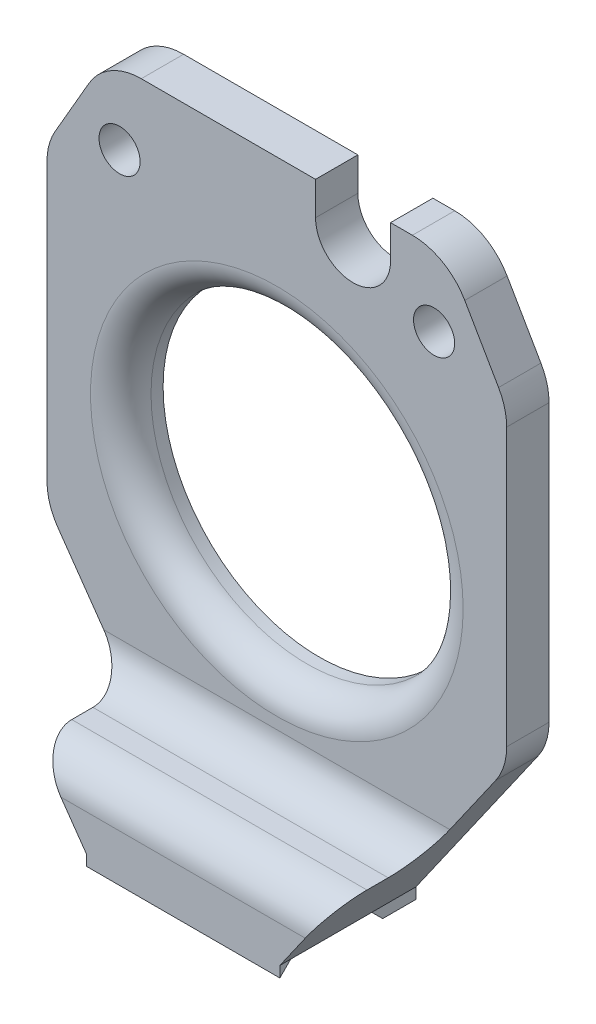
SolidWorks part; units mm, degrees
ref_plane "Front Plane" through (0, 0, 0) normal (0, 0, 1) x (1, 0, 0)
ref_plane "Top Plane" through (0, 0, 0) normal (0, 1, 0) x (1, 0, 0)
ref_plane "Right Plane" through (0, 0, 0) normal (1, 0, 0) x (0, 0, -1)
sketch "Sketch1" plane through (0, 0, 0) normal (0, 0, 1) x (1, 0, 0)
  line L0 (-19, -8.2904) -> (-19, 17.5)
  line L1 (-19, 17.5) -> (-14.0925, 26)
  line L2 (-14.0925, 26) -> (14.0925, 26)
  line L3 (14.0925, 26) -> (19, 17.5)
  line L4 (19, 17.5) -> (19, -8.2904)
  line L5 (-13, 20) -> (13, 20) construction
  line L6 (-19, -8.2904) -> (-8, -24)
  line L7 (-8, -24) -> (8, -24)
  line L8 (8, -24) -> (19, -8.2904)
  line L9 (-19, 17.5) -> (19, 17.5) construction
  line L10 (-19, -8.2904) -> (19, -8.2904) construction
  line L11 (0, 0) -> (0, 1.35) construction
  circle A1 centre (-13, 20) radius 1.7
  circle A2 centre (13, 20) radius 1.7
  circle A3 centre (0, 1.35) radius 12.9
  dimension "D2" = 20
  dimension "D9" = 3.4
  dimension "D10" = 3.4
  dimension "D11" = 8.2904
  dimension "D12" = 26
  dimension "D13" = 13
  dimension "D16" = 25.8
  dimension "D3" = 26
  dimension "D4" = 17.5
  dimension "D5" = 19
  dimension "D6" = 24
  dimension "D7" = 30
  dimension "D8" = 30
  dimension "D14" = 16
  dimension "D15" = 18.65
  dimension "D17" = 35
  dimension "D18" = 35
extrude "Boss-Extrude1" add sketch "Sketch1" along normal blind 3.5
fillet "Fillet1" radius 2.5 1 edges at (12.9, 1.35, 3.5)
fillet "Fillet2" radius 5 6 edges at (19, -8.2904, 1.75) (19, 17.5, 1.75) (-19, -8.2904, 1.75) (-19, 17.5, 1.75) (-14.0925, 26, 1.75) (14.0925, 26, 1.75)
sketch "Sketch2" plane through (0, 0, 3.5) normal (0, 0, 1) x (1, 0, 0)
  line L0 (-12.2012, -18) -> (-8, -24)
  line L1 (-18.0958, -9.5818) -> (-8, -24) construction
  line L2 (-8, -24) -> (8, -24)
  line L3 (8, -24) -> (12.2012, -18)
  line L4 (8, -24) -> (18.0958, -9.5818) construction
  line L5 (12.2012, -18) -> (-12.2012, -18)
  dimension "D1" = 6
extrude "Boss-Extrude2" add sketch "Sketch2" along normal blind 7.75
fillet "Fillet3" radius 3 2 edges at (0, -18, 11.25) (0, -18, 3.5)
sketch "Sketch3" plane through (0, -24, 0) normal (0, -1, 0) x (1, 0, 0)
  line L0 (0, 0) -> (0, 11.25) construction
  line L1 (-8, 11.25) -> (8, 11.25) construction
  line L2 (-4.25, 7) -> (4.25, 7) construction
  line L3 (-8, 0) -> (8, 0) construction
  circle A0 centre (-4.25, 7) radius 3.2
  circle A1 centre (4.25, 7) radius 3.2
  dimension "D4" = 6.4
  dimension "D5" = 6.4
  dimension "D1" = 8.5
  dimension "D2" = 4.25
  dimension "D3" = 7
extrude "Cut-Extrude1" cut sketch "Sketch3" against normal blind 3.1
sketch "Sketch4" plane through (0, -20.9, 0) normal (0, -1, 0) x (1, 0, 0)
  circle A0 centre (-4.25, 7) radius 2
  circle A1 centre (4.25, 7) radius 2
  dimension "D1" = 4
  dimension "D2" = 4
extrude "Cut-Extrude2" cut sketch "Sketch4" against normal blind 1.75
sketch "Sketch5" plane through (0, 0, 0) normal (0, 0, -1) x (-1, 0, 0)
  line L0 (0, -24) -> (0, -9.4889) construction
  line L1 (8, -24) -> (-8, -24) construction
  line L2 (-4.25, -20.225) -> (4.25, -20.225) construction
  circle A0 centre (4.25, -20.225) radius 0.85
  circle A1 centre (-4.25, -20.225) radius 0.85
  dimension "D4" = 1.7
  dimension "D5" = 1.7
  dimension "D1" = 3.775
  dimension "D2" = 8.5
  dimension "D3" = 4.25
extrude "Cut-Extrude3" cut sketch "Sketch5" against normal blind 7
sketch "Sketch6" plane through (0, 0, 0) normal (0, 0, -1) x (-1, 0, 0)
  line L15 (18.3301, 18.6603) -> (16.5981, 21.6603)
  line L16 (-5.1, -20.225) -> (-5.1, -20.075)
  line L17 (14.6383, -7.5457) -> (7.8628, -17.2222)
  line L18 (15, 18.3564) -> (15, -6.3986)
  line L19 (16.5981, 21.6603) -> (15.2679, 19.3564)
  line L20 (18.2679, 18.5526) -> (18.3301, 18.6603)
  line L21 (18, -7.3445) -> (18, 17.5526)
  line L22 (9.4245, -20.2222) -> (17.6383, -8.4916)
  line L23 (4.25, -21.075) -> (7.7862, -21.075)
  line L24 (6.2245, -18.075) -> (-3.1, -18.075)
  line L25 (4.25, -21.075) -> (-4.25, -21.075)
  arc A12 (18, 17.5526) -> (18.2679, 18.5526) centre (20, 17.5526) cw
  arc A13 (15.2679, 19.3564) -> (15, 18.3564) centre (17, 18.3564) ccw
  arc A14 (15, -6.3986) -> (14.6383, -7.5457) centre (13, -6.3986) cw
  arc A15 (17.6383, -8.4916) -> (18, -7.3445) centre (16, -7.3445) ccw
  arc A16 (7.7862, -21.075) -> (9.4245, -20.2222) centre (7.7862, -19.075) ccw
  arc A17 (6.2245, -18.075) -> (7.8628, -17.2222) centre (6.2245, -16.075) ccw
  arc A18 (-3.1, -18.075) -> (-5.1, -20.075) centre (-3.1, -20.075) ccw
  arc A19 (-4.25, -21.075) -> (-5.1, -20.225) centre (-4.25, -20.225) cw
extrude "Cut-Extrude4" cut sketch "Sketch6" against normal blind 2
ref_plane "Plane1" through (8, 0, 0) normal (1, 0, 0) x (0, 0, -1)
sketch "Sketch7" plane through (8, 0, 0) normal (1, 0, 0) x (0, 0, -1)
  line L0 (-11.25, -24) -> (-11.25, -24.9)
  line L1 (-11.25, -24.9) -> (-10.35, -24)
  line L2 (-10.35, -24) -> (-11.25, -24)
  line L4 (-2.75, -24.9) -> (-3.65, -24)
  line L5 (-11.25, -24) -> (0, -24) construction
  line L7 (-2.75, -24.9) -> (0, -24.9)
  line L8 (0, -24.9) -> (0, -24)
  line L9 (0, -24) -> (-3.65, -24)
  point P8 (0, 0)
  dimension "D1" = 45
  dimension "D2" = 8.5
  dimension "D3" = 0.9
extrude "Boss-Extrude3" add sketch "Sketch7" against normal up to vertex (16 mm away)
sketch "Sketch9" plane through (0, 0, 3.5) normal (0, 0, 1) x (1, 0, 0)
  line L0 (3.2, 23.25) -> (3.2, 26)
  line L1 (11.2058, 26) -> (-11.2058, 26) construction
  line L2 (3.2, 26) -> (9.4, 26)
  line L3 (9.4, 26) -> (9.4, 23.25)
  arc A0 (3.2, 23.25) -> (9.4, 23.25) centre (6.3, 23.25) ccw
  circle A1 centre (13, 20) radius 1.7 construction
  dimension "D1" = 3.25
  dimension "D2" = 6.7
  dimension "D3" = 6.2
extrude "Cut-Extrude5" cut sketch "Sketch9" against normal through all
